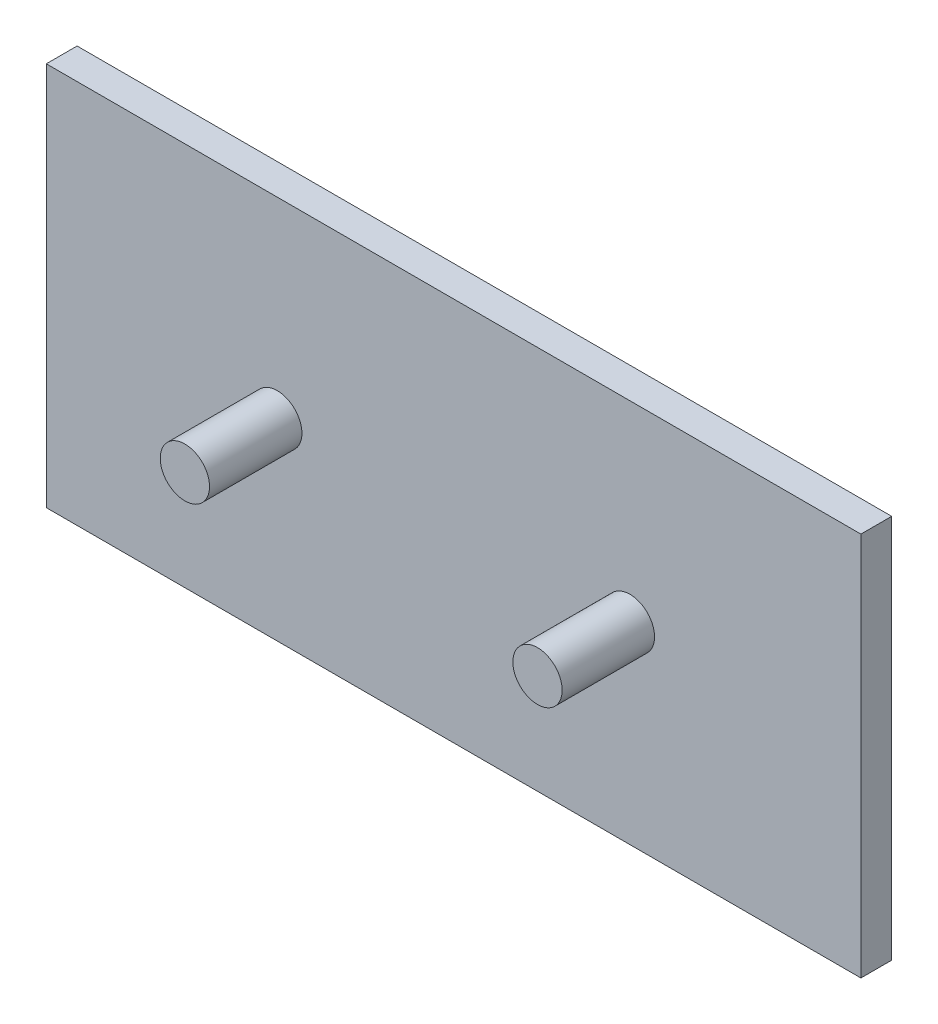
SolidWorks part; units mm, degrees
ref_plane "Front Plane" through (0, 0, 0) normal (0, 0, 1) x (1, 0, 0)
ref_plane "Top Plane" through (0, 0, 0) normal (0, 1, 0) x (1, 0, 0)
ref_plane "Right Plane" through (0, 0, 0) normal (1, 0, 0) x (0, 0, -1)
sketch "Sketch1" plane through (0, 0, 0) normal (0, 0, 1) x (1, 0, 0)
  line L1 (-55.5277, 30.9251) -> (76.6942, 30.9251)
  line L2 (-55.5277, 30.9251) -> (-55.5277, -31.4748)
  line L3 (-55.5277, -31.4748) -> (76.6942, -31.4748)
  line L4 (76.6942, 30.9251) -> (76.6942, -31.4748)
extrude "Boss-Extrude1" add sketch "Sketch1" along normal blind 5
sketch "Sketch2" plane through (0, 0, 5) normal (0, 0, 1) x (1, 0, 0)
  line L0 (-55.5277, -0.2749) -> (76.6942, -0.2749) construction
  line L1 (-55.5277, 30.9251) -> (-55.5277, -31.4748) construction
  line L2 (76.6942, -31.4748) -> (76.6942, 30.9251) construction
  line L3 (10.5832, 30.9251) -> (10.5832, -31.4748) construction
  line L4 (76.6942, 30.9251) -> (-55.5277, 30.9251) construction
  line L5 (-55.5277, -31.4748) -> (76.6942, -31.4748) construction
  circle A0 centre (-18.036, -0.2749) radius 4
  circle A1 centre (39.2025, -0.2749) radius 4
  dimension "D1" = 8
extrude "Boss-Extrude2" add sketch "Sketch2" along normal blind 15
